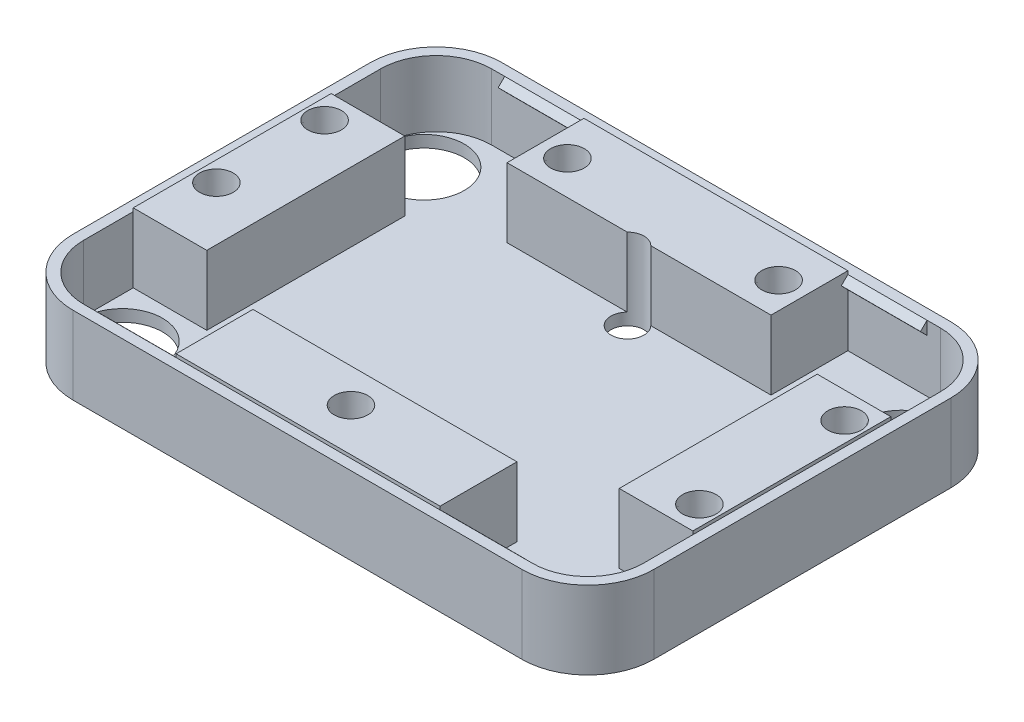
SolidWorks part; units mm, degrees
ref_plane "Front Plane" through (0, 0, 0) normal (0, 0, 1) x (1, 0, 0)
ref_plane "Top Plane" through (0, 0, 0) normal (0, 1, 0) x (1, 0, 0)
ref_plane "Right Plane" through (0, 0, 0) normal (1, 0, 0) x (0, 0, -1)
sketch "Sketch1" plane through (0, 0, 0) normal (0, 1, 0) x (1, 0, 0)
  line L1 (0, 0) -> (88, 0)
  line L2 (0, 0) -> (0, 65)
  line L3 (0, 65) -> (88, 65)
  line L4 (88, 0) -> (88, 65)
  dimension "D1" = 88
  dimension "D2" = 65
extrude "Boss-Extrude2" add sketch "Sketch1" along normal blind 1.8
fillet "Fillet1" radius 10 4 edges at (0, 0.9, 0) (0, 0.9, -65) (88, 0.9, -65) (88, 0.9, 0)
hole_wizard "Ø12.2 (12.2) Diameter Hole1" positions "Sketch2" profile "Sketch3" hole size "Ø12.2" standard "ANSI Metric" end condition through all
sketch "Sketch2" plane through (0, 1.8, 0) normal (0, 1, 0) x (1, 0, 0)
  line L0 (44, 65) -> (44, 0) construction
  line L1 (78, 65) -> (10, 65) construction
  line L2 (10, 0) -> (78, 0) construction
  line L4 (7.805, 55.36) -> (80.195, 55.36) construction
  line L6 (0, 32.5) -> (88, 32.5) construction
  line L7 (0, 55) -> (0, 10) construction
  line L8 (88, 10) -> (88, 55) construction
  line L10 (80.195, 55.36) -> (80.195, 9.64) construction
  point P0 (7.805, 55.36)
  point P2 (80.195, 55.36)
  point P4 (7.805, 9.64)
  point P6 (80.195, 9.64)
  point P28 (44, 55.36)
  point P44 (80.195, 32.5)
  dimension "D1" = 72.39
  dimension "D2" = 45.72
sketch "Sketch3" plane through (7.805, 1.8, -55.36) normal (1, 0, 0) x (0, 0, 1)
  line L0 (0, 0) -> (0, 1.8)
  line L1 (0, 1.8) -> (6.1, 1.8)
  line L2 (6.1, 1.8) -> (6.1, 0)
  line L5 (6.1, 0) -> (0, 0)
  line L11 (0, -6.35) -> (0, 107.95) construction
  dimension "Thru Hole Dia." = 12.2
  dimension "Thru Hole Depth" = 1.8
sketch "Sketch4" plane through (0, 1.8, 0) normal (0, 1, 0) x (1, 0, 0)
  line L5 (78, 65) -> (10, 65) construction
  line L6 (0, 55) -> (0, 10) construction
  line L7 (10, 0) -> (78, 0) construction
  line L8 (78, 63.4) -> (10, 63.4)
  line L9 (1.6, 55) -> (1.6, 10)
  line L10 (10, 1.6) -> (78, 1.6)
  line L11 (86.4, 10) -> (86.4, 55)
  line L12 (78, 63.4) -> (10, 63.4)
  line L13 (1.6, 55) -> (1.6, 10)
  line L14 (10, 1.6) -> (78, 1.6)
  line L15 (86.4, 10) -> (86.4, 55)
  line L16 (88, 10) -> (88, 55) construction
  line L17 (78, 65) -> (10, 65)
  line L18 (0, 55) -> (0, 10)
  line L19 (10, 0) -> (78, 0)
  line L20 (88, 10) -> (88, 55)
  arc A4 (88, 55) -> (78, 65) centre (78, 55) ccw construction
  arc A5 (10, 65) -> (0, 55) centre (10, 55) ccw construction
  arc A6 (0, 10) -> (10, 0) centre (10, 10) ccw construction
  arc A7 (78, 0) -> (88, 10) centre (78, 10) ccw construction
  arc A8 (86.4, 55) -> (78, 63.4) centre (78, 55) ccw
  arc A9 (10, 63.4) -> (1.6, 55) centre (10, 55) ccw
  arc A10 (1.6, 10) -> (10, 1.6) centre (10, 10) ccw
  arc A11 (78, 1.6) -> (86.4, 10) centre (78, 10) ccw
  arc A12 (86.4, 55) -> (78, 63.4) centre (78, 55) ccw
  arc A13 (10, 63.4) -> (1.6, 55) centre (10, 55) ccw
  arc A14 (1.6, 10) -> (10, 1.6) centre (10, 10) ccw
  arc A15 (78, 1.6) -> (86.4, 10) centre (78, 10) ccw
  arc A16 (88, 55) -> (78, 65) centre (78, 55) ccw
  arc A17 (10, 65) -> (0, 55) centre (10, 55) ccw
  arc A18 (0, 10) -> (10, 0) centre (10, 10) ccw
  arc A19 (78, 0) -> (88, 10) centre (78, 10) ccw
  dimension "D1" = 1.6
extrude "Boss-Extrude3" add sketch "Sketch4" along normal blind 10
sketch "Sketch5" plane through (0, 1.8, 0) normal (0, 1, 0) x (1, 0, 0)
  line L0 (44, 63.4) -> (44, 1.6) construction
  line L1 (24, 51.75) -> (64, 51.75)
  line L2 (24, 51.75) -> (24, 63.4)
  line L3 (24, 63.4) -> (64, 63.4)
  line L4 (64, 51.75) -> (64, 63.4)
  line L5 (24, 13.25) -> (64, 13.25)
  line L6 (24, 13.25) -> (24, 1.6)
  line L7 (24, 1.6) -> (64, 1.6)
  line L8 (64, 13.25) -> (64, 1.6)
  line L9 (75.25, 47.5) -> (86.4, 47.5)
  line L10 (75.25, 47.5) -> (75.25, 17.5)
  line L11 (75.25, 17.5) -> (86.4, 17.5)
  line L12 (86.4, 47.5) -> (86.4, 17.5)
  line L13 (1.6, 47.5) -> (12.75, 47.5)
  line L14 (1.6, 47.5) -> (1.6, 17.5)
  line L15 (1.6, 17.5) -> (12.75, 17.5)
  line L16 (12.75, 47.5) -> (12.75, 17.5)
  line L17 (78, 63.4) -> (10, 63.4) construction
  line L18 (10, 1.6) -> (78, 1.6) construction
  line L19 (1.6, 32.5) -> (86.4, 32.5) construction
  line L20 (1.6, 55) -> (1.6, 10) construction
  line L21 (86.4, 10) -> (86.4, 55) construction
  line L22 (10, 1.6) -> (78, 1.6) construction
  point P28 (44, 63.4)
  point P31 (12.75, 32.5)
  dimension "D1" = 38.5
  dimension "D2" = 62.5
  dimension "D3" = 40
  dimension "D4" = 30
extrude "Boss-Extrude4" add sketch "Sketch5" along normal blind 10.5
sketch "Sketch6" plane through (0, 12.3, 0) normal (0, 1, 0) x (1, 0, 0)
  circle A0 centre (28, 56.9) radius 2.5 construction
  circle A1 centre (28, 56.9) radius 2.5
  circle A2 centre (60, 56.9) radius 2.5 construction
  circle A3 centre (60, 56.9) radius 2.5
  circle A4 centre (83.4, 43.5) radius 2.5 construction
  circle A5 centre (83.4, 43.5) radius 2.5
  circle A6 centre (83.4, 21.5) radius 2.5 construction
  circle A7 centre (83.4, 21.5) radius 2.5
  circle A8 centre (44, 8.1) radius 2.5 construction
  circle A9 centre (44, 8.1) radius 2.5
  circle A10 centre (4.6, 27.1063) radius 2.5 construction
  circle A11 centre (4.6, 27.1063) radius 2.5
  circle A12 centre (4.6, 43.5) radius 2.5 construction
  circle A13 centre (4.6, 43.5) radius 2.5
  circle A14 centre (60, 56.9) radius 2.55
  circle A15 centre (28, 56.9) radius 2.55
  circle A16 centre (4.6, 43.5) radius 2.55
  circle A17 centre (4.6, 27.1063) radius 2.55
  circle A18 centre (83.4, 21.5) radius 2.55
  circle A19 centre (83.4, 43.5) radius 2.55
  circle A20 centre (44, 8.1) radius 2.55
  dimension "D1" = 0.05
extrude "Cut-Extrude1" cut sketch "Sketch6" against normal blind 5 draft 2 contours A1 | A15 A1 | A3 | A14 A3 | A5 | A19 A5 | A7 | A18 A7 | A9 | A20 A9 | A11 | A17 A11 | A13 | A16 A13
sketch "Sketch7" plane through (0, 0, 0) normal (0, -1, 0) x (1, 0, 0)
  line L2 (88, -50) -> (0, -50) construction
  line L3 (88, -10) -> (88, -55) construction
  line L4 (0, -55) -> (0, -10) construction
  line L5 (78, -65) -> (10, -65) construction
  circle A0 centre (44, -50) radius 2.5
  point P2 (0, 0)
  dimension "D1" = 5
  dimension "D2" = 15
extrude "Cut-Extrude2" cut sketch "Sketch7" against normal through all
sketch "Sketch8" plane through (24, 0, 0) normal (-1, 0, 0) x (0, 0, 1)
  line L0 (-1.6, 11.8) -> (-2.6, 10.8215)
  line L1 (-2.6, 10.8215) -> (-1.6, 9.7995)
  line L2 (-1.6, 11.8) -> (-1.6, 1.8) construction
  line M2 (-1.6, 1.8) -> (-1.6, 11.8)
  dimension "D1" = 1
extrude "Boss-Extrude5" add sketch "Sketch8" along normal blind 12 contours L0 L1 M2
ref_plane "Plane1" through (44, 0, 0) normal (-1, 0, 0) x (0, 0, 1)
ref_plane "Plane2" through (0, 0, -32.5) normal (0, 0, 1) x (1, 0, 0)
mirror "Mirror1" about plane through (0, 0, -32.5) normal (0, 0, 1) of "Boss-Extrude5" second plane through (44, 0, 0) second plane normal (-1, 0, 0)
